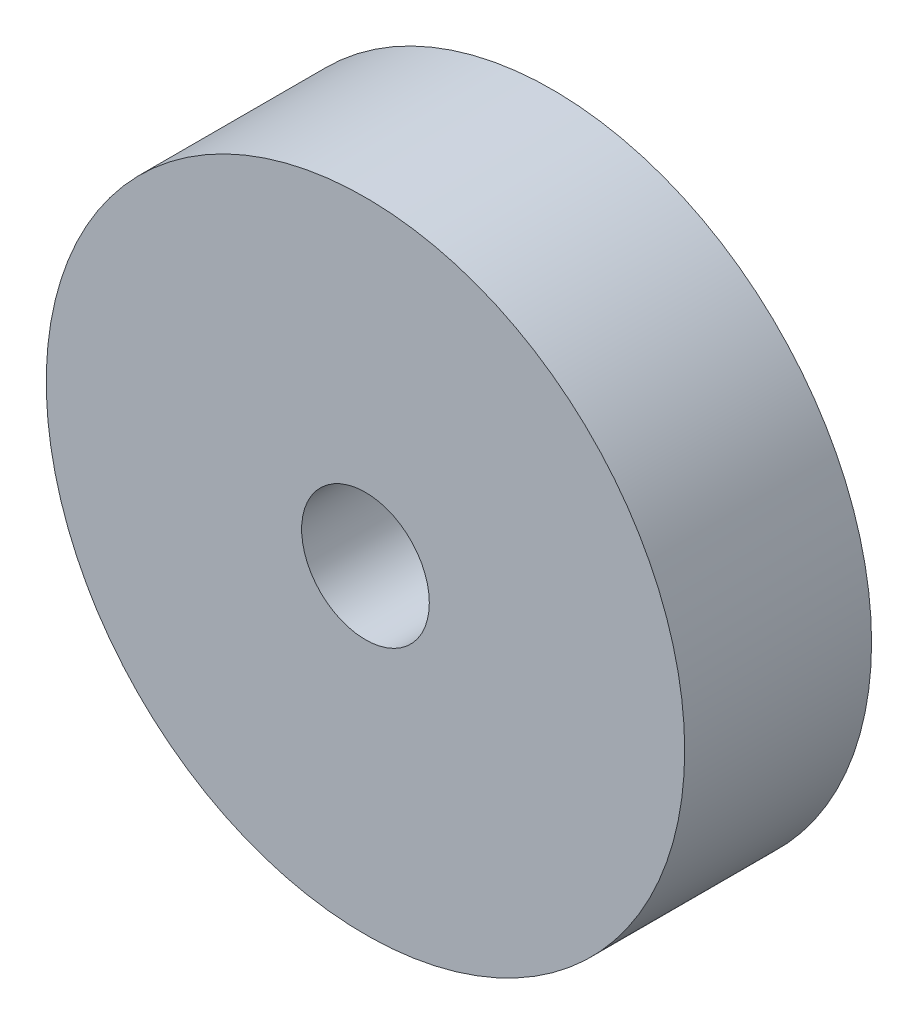
SolidWorks part; units mm, degrees
ref_plane "前视基准面" through (0, 0, 0) normal (0, 0, 1) x (1, 0, 0)
ref_plane "上视基准面" through (0, 0, 0) normal (0, 1, 0) x (1, 0, 0)
ref_plane "右视基准面" through (0, 0, 0) normal (1, 0, 0) x (0, 0, -1)
sketch "草图1" plane through (0, 0, 0) normal (0, 0, 1) x (1, 0, 0)
  circle A0 centre (0, 0) radius 20.5
  circle A1 centre (0, 0) radius 4.1
  dimension "D1" = 41
  dimension "D2" = 8.2
extrude "凸台-拉伸1" add sketch "草图1" along normal blind 12
